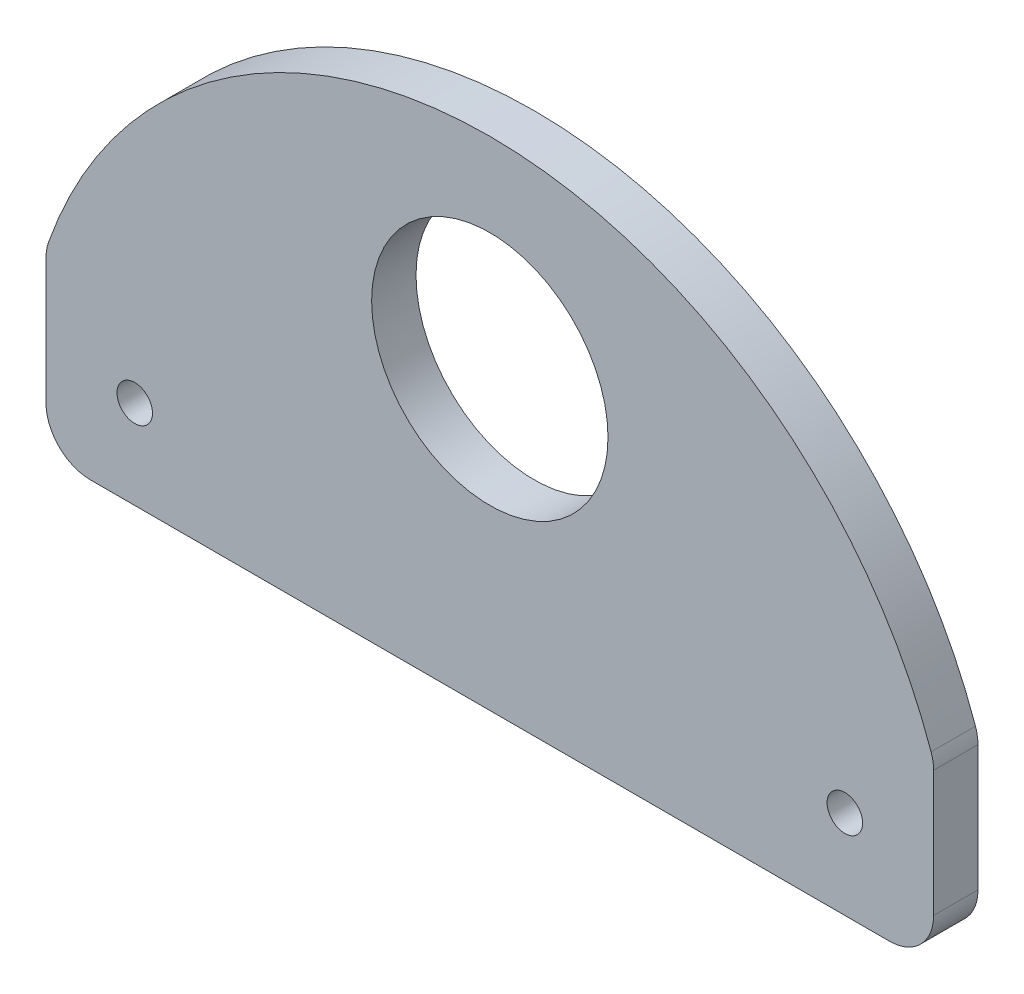
SolidWorks part; units mm, degrees
ref_plane "Plan de face" through (0, 0, 0) normal (0, 0, 1) x (1, 0, 0)
ref_plane "Plan de dessus" through (0, 0, 0) normal (0, 1, 0) x (1, 0, 0)
ref_plane "Plan de droite" through (0, 0, 0) normal (1, 0, 0) x (0, 0, -1)
sketch "Esquisse2" plane through (0, 0, 0) normal (0, 0, 1) x (1, 0, 0)
  line L0 (-50, 20) -> (-50, 0)
  line L1 (-50, 0) -> (50, 0)
  line L2 (0, 0) -> (0, 59.3574) construction
  line L3 (50, 20) -> (50, 0)
  line L4 (-50, 10) -> (50, 10) construction
  line L5 (-50, 20) -> (50, 20) construction
  arc A0 (-50, 20) -> (50, 20) centre (0, 3.315) cw
  circle A1 centre (-40, 10) radius 2
  circle A2 centre (40, 10) radius 2
  circle A3 centre (0, 33.315) radius 13.315
  dimension "D1" = 20
  dimension "D3" = 4
  dimension "D5" = 26.63
  dimension "D6" = 30
  dimension "D2" = 100
  dimension "D4" = 80
extrude "Boss.-Extru.1" add sketch "Esquisse2" along normal blind 5
fillet "Congé1" radius 5 4 edges at (50, 20, 2.5) (-50, 20, 2.5) (-50, 0, 2.5) (50, 0, 2.5)
